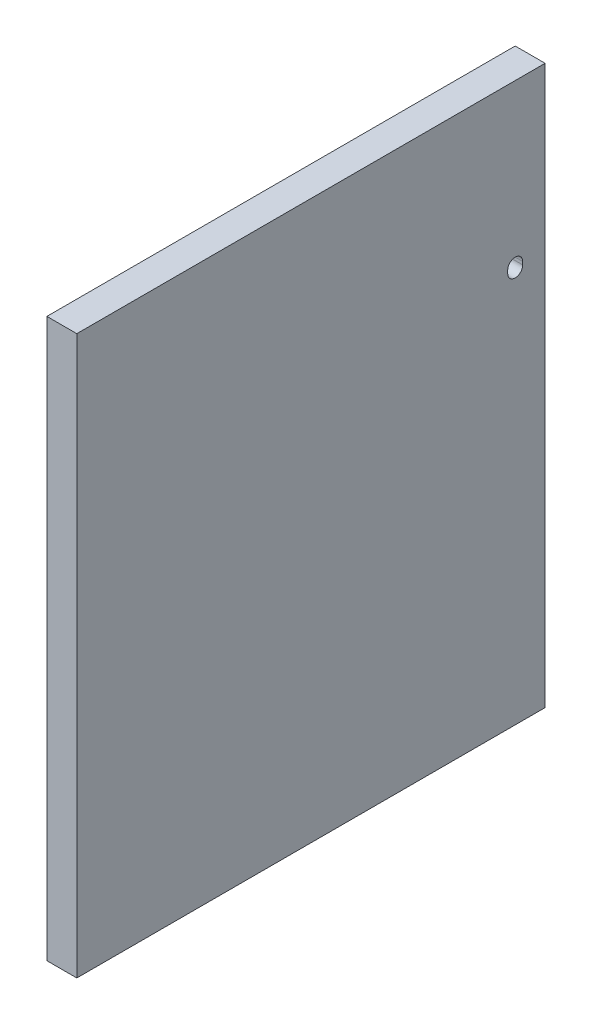
SolidWorks part; units mm, degrees
ref_plane "Front Plane" through (0, 0, 0) normal (0, 0, 1) x (1, 0, 0)
ref_plane "Top Plane" through (0, 0, 0) normal (0, 1, 0) x (1, 0, 0)
ref_plane "Right Plane" through (0, 0, 0) normal (1, 0, 0) x (0, 0, -1)
other "Configuration Table"
sketch "Sketch1" plane through (0, 0, 0) normal (1, 0, 0) x (0, 0, -1)
  line L1 (-149.6045, 68.7233) -> (49.1565, 68.7233)
  line L2 (-149.6045, 68.7233) -> (-149.6045, -168.1101)
  line L3 (-149.6045, -168.1101) -> (49.1565, -168.1101)
  line L4 (49.1565, 68.7233) -> (49.1565, -168.1101)
  point P0 (0, 0)
extrude "Boss-Extrude1" add sketch "Sketch1" along normal blind 12.7
sketch "Sketch2" plane through (0, 0, 0) normal (-1, 0, 0) x (0, 0, 1)
  line L0 (-36.4565, 0.635) -> (-36.4565, -0.635) construction
  line L1 (-33.2815, 0.635) -> (-33.2815, -0.635)
  line L2 (-39.6315, 0.635) -> (-39.6315, -0.635)
  line L4 (-49.1565, -168.1101) -> (-49.1565, 68.7233) construction
  line L5 (-36.4565, 0) -> (-35.6676, 0) construction
  arc A0 (-33.2815, 0.635) -> (-39.6315, 0.635) centre (-36.4565, 0.635) ccw
  arc A1 (-39.6315, -0.635) -> (-33.2815, -0.635) centre (-36.4565, -0.635) ccw
  point P2 (-36.4565, 0)
  dimension "D1" = 7.62
  dimension "D2" = 6.35
  dimension "D3" = 12.7
extrude "Cut-Extrude1" cut sketch "Sketch2" against normal blind 12.7
fillet "Fillet1" radius 3 4 edges at (0, 0, -33.2815) (0, -3.81, -36.4565) (0, 0, -39.6315) (0, 3.81, -36.4565)
